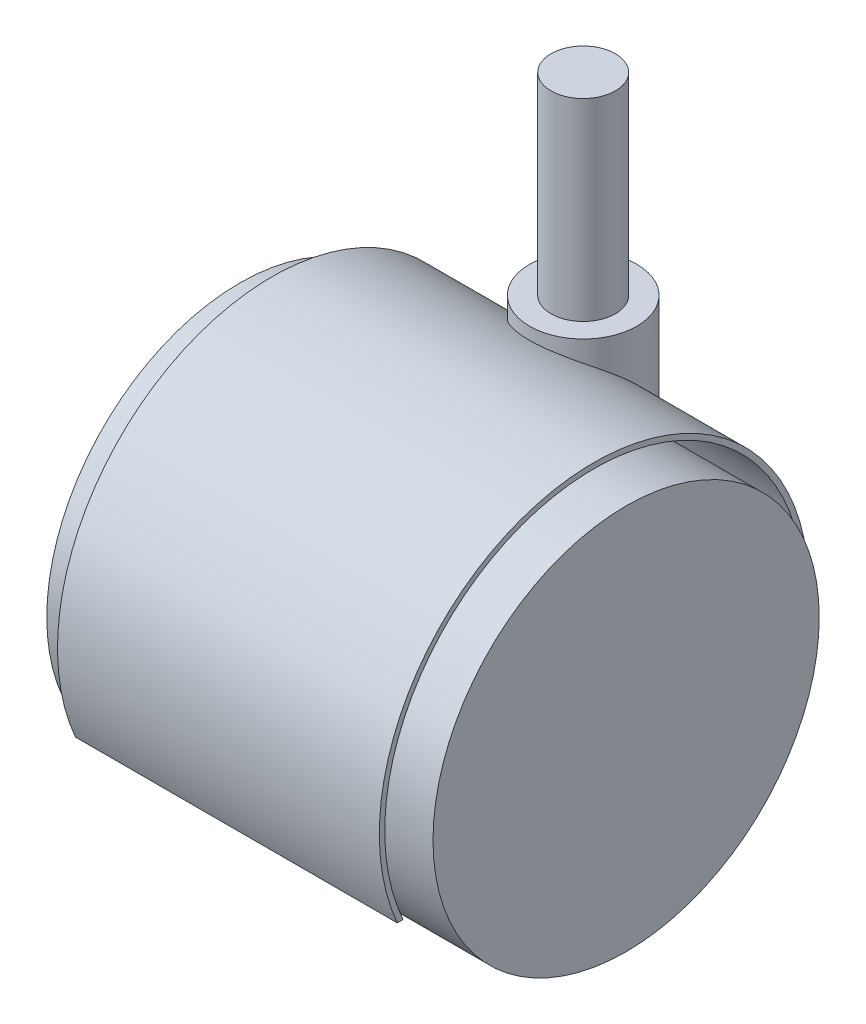
SolidWorks part; units mm, degrees
ref_plane "Plan de face" through (0, 0, 0) normal (0, 0, 1) x (1, 0, 0)
ref_plane "Plan de dessus" through (0, 0, 0) normal (0, 1, 0) x (1, 0, 0)
ref_plane "Plan de droite" through (0, 0, 0) normal (1, 0, 0) x (0, 0, -1)
sketch "Esquisse1" plane through (0, 0, 0) normal (1, 0, 0) x (0, 0, -1)
  line L0 (0, 20) -> (0, -8) construction
  line L1 (-21.1007, -8) -> (23.9003, -8) construction
  line L2 (-18.3303, -8) -> (18.3303, -8)
  arc A0 (18.3303, -8) -> (-18.3303, -8) centre (0, 0) ccw
  dimension "D1" = 40
  dimension "D2" = 28
extrude "BASE ROUE" add sketch "Esquisse1" along normal blind 15
sketch "Esquisse2" plane through (15, 0, 0) normal (1, 0, 0) x (0, 0, -1)
  circle A0 centre (0, 0) radius 19.5
  arc A1 (18.3303, -8) -> (-18.3303, -8) centre (0, 0) ccw construction
  dimension "D1" = 0.5
extrude "VIDE ROUE" cut sketch "Esquisse2" against normal blind 13
sketch "Esquisse3" plane through (2, 0, 0) normal (1, 0, 0) x (0, 0, -1)
  circle A0 centre (0, 0) radius 4.5
  arc A1 (17.7834, -8) -> (-17.7834, -8) centre (0, 0) ccw construction
  dimension "D1" = 15
extrude "AXE ROUE" add sketch "Esquisse3" along normal blind 5
sketch "Esquisse4" plane through (7, 0, 0) normal (1, 0, 0) x (0, 0, -1)
  circle A0 centre (0, 0) radius 18
  arc A1 (18.3303, -8) -> (-18.3303, -8) centre (0, 0) ccw construction
  dimension "D1" = 2
extrude "ROUE" add sketch "Esquisse4" along normal blind 11
mirror "SYM ROUE + BASE" about plane through (0, 0, 0) normal (1, 0, 0) of "ROUE", "AXE ROUE", "BASE ROUE", "VIDE ROUE"
ref_plane "PLAN VIS" through (0, 5, 0) normal (0, 1, 0) x (1, 0, 0)
sketch "Esquisse6" plane through (0, 5, 0) normal (0, 1, 0) x (1, 0, 0)
  line L0 (-11.0636, 0) -> (12.6034, 0) construction
  circle A0 centre (0, 14) radius 5
  point P3 (0, 14)
  dimension "D2" = 10
  dimension "D1" = 14
extrude "VIS" add sketch "Esquisse6" along normal blind 32
sketch "Esquisse7" plane through (0, 37, 0) normal (0, 1, 0) x (1, 0, 0)
  circle A0 centre (0, 14) radius 5
  circle A1 centre (0, 14) radius 3
  dimension "D1" = 6
extrude "Enlèv. mat.-Extru.3" cut sketch "Esquisse7" against normal blind 18
